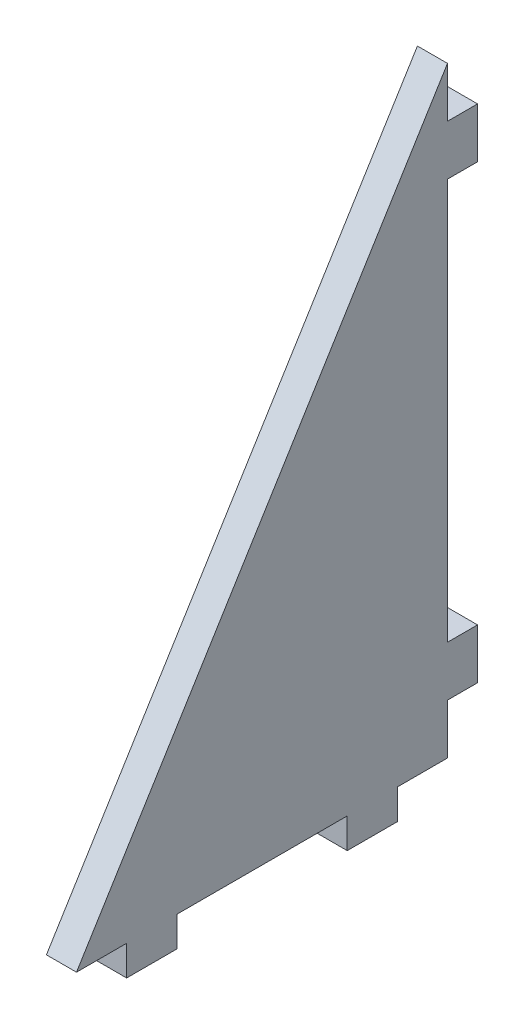
SolidWorks part; units mm, degrees
ref_plane "Front Plane" through (0, 0, 0) normal (0, 0, 1) x (1, 0, 0)
ref_plane "Top Plane" through (0, 0, 0) normal (0, 1, 0) x (1, 0, 0)
ref_plane "Right Plane" through (0, 0, 0) normal (1, 0, 0) x (0, 0, -1)
sketch "Sketch1" plane through (0, 0, 0) normal (1, 0, 0) x (0, 0, -1)
  line L1 (-18.5, -30) -> (18.5, -30)
  line L2 (-18.5, -30) -> (-18.5, 30)
  line L3 (-18.5, 30) -> (18.5, 30)
  line L4 (18.5, -30) -> (18.5, 30)
  line L5 (0, 30) -> (0, -30) construction
  line L6 (-18.5, 0) -> (18.5, 0) construction
  point P0 (0, 0)
  dimension "D1" = 60
  dimension "D2" = 37
extrude "Boss-Extrude1" add sketch "Sketch1" along normal blind 3
sketch "Sketch2" plane through (3, 0, 0) normal (1, 0, 0) x (0, 0, -1)
  line L0 (-18.5, -30) -> (18.5, 30)
  line L1 (18.5, 30) -> (-18.5, 30)
  line L2 (-18.5, 30) -> (-18.5, -30)
extrude "Cut-Extrude1" cut sketch "Sketch2" against normal blind 3
sketch "Sketch3" plane through (0, -30, 0) normal (0, -1, 0) x (1, 0, 0)
  line L0 (0, 18.5) -> (0, -18.5) construction
  line L1 (0, 13.5) -> (3, 13.5)
  line L2 (0, 13.5) -> (0, 8.5)
  line L3 (0, 8.5) -> (3, 8.5)
  line L4 (3, 13.5) -> (3, 8.5)
  line L5 (3, 18.5) -> (3, -18.5) construction
  line L6 (3, 18.5) -> (0, 18.5) construction
  line L7 (3, -8.5) -> (0, -8.5)
  line L8 (3, -8.5) -> (3, -13.5)
  line L9 (3, -13.5) -> (0, -13.5)
  line L10 (0, -8.5) -> (0, -13.5)
  line L11 (3, -18.5) -> (0, -18.5) construction
  dimension "D1" = 5
  dimension "D2" = 5
  dimension "D3" = 5
  dimension "D4" = 5
extrude "Boss-Extrude2" add sketch "Sketch3" along normal blind 3
sketch "Sketch4" plane through (0, 0, -18.5) normal (0, 0, -1) x (-1, 0, 0)
  line L0 (-3, -30) -> (-3, 30) construction
  line L1 (-3, -25) -> (0, -25)
  line L2 (-3, -25) -> (-3, -20)
  line L3 (-3, -20) -> (0, -20)
  line L4 (0, -25) -> (0, -20)
  line L5 (0, -30) -> (0, 30) construction
  line L6 (-3, -30) -> (0, -30) construction
  line L7 (-3, 20) -> (0, 20)
  line L8 (-3, 20) -> (-3, 25)
  line L9 (-3, 25) -> (0, 25)
  line L10 (0, 20) -> (0, 25)
  line L11 (-3, 30) -> (0, 30) construction
  dimension "D1" = 5
  dimension "D2" = 5
  dimension "D3" = 5
  dimension "D4" = 5
extrude "Boss-Extrude3" add sketch "Sketch4" along normal blind 3
